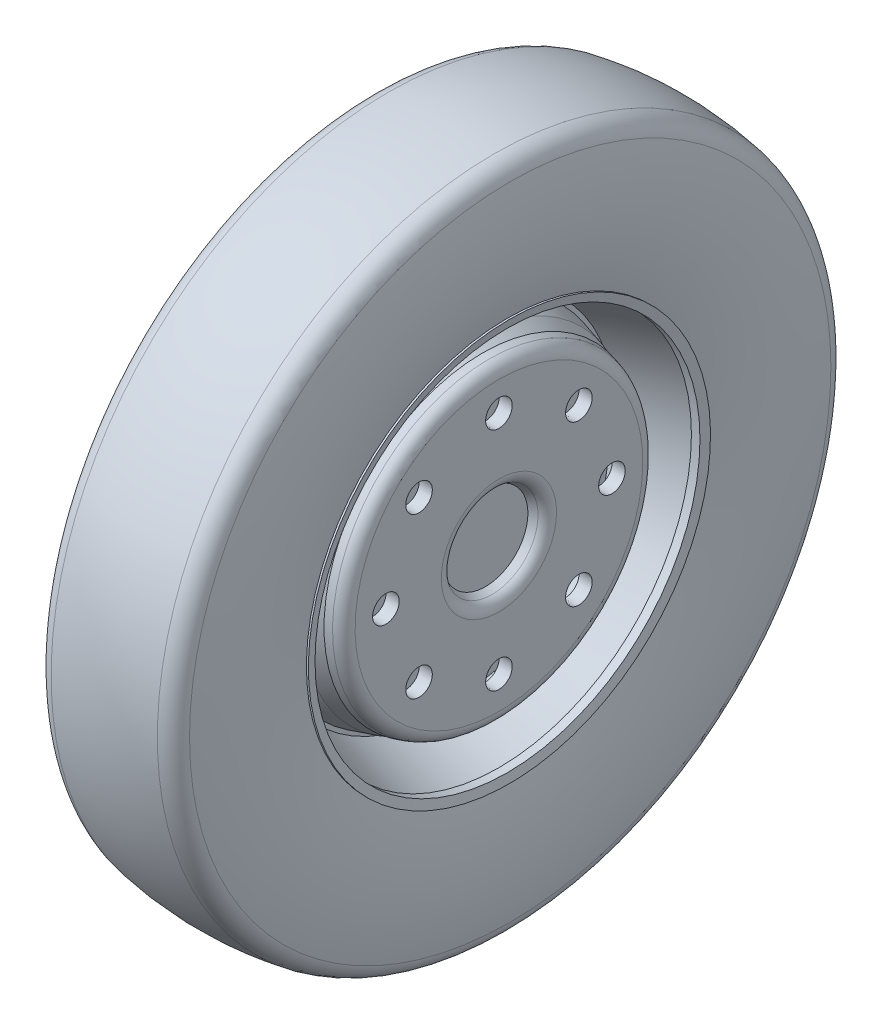
SolidWorks part; units mm, degrees
ref_plane "Front Plane" through (0, 0, 0) normal (0, 0, 1) x (1, 0, 0)
ref_plane "Top Plane" through (0, 0, 0) normal (0, 1, 0) x (1, 0, 0)
ref_plane "Right Plane" through (0, 0, 0) normal (1, 0, 0) x (0, 0, -1)
sketch "Sketch2" plane through (0, 0, 0) normal (0, 0, 1) x (1, 0, 0)
  line L0 (0, 300) -> (0, 212.5441)
  line L1 (0, 300) -> (-28.5605, 300)
  line L2 (-53.1832, 300) -> (-53.1832, 500) construction
  line L3 (-53.1832, 500) -> (146.8168, 500) construction
  line L4 (146.8168, 500) -> (146.8168, 300) construction
  line L5 (46.8168, 259.1719) -> (46.8168, 245.2638)
  line L6 (46.8168, -2.4559) -> (25, -2.4559)
  line L7 (46.8168, 259.1719) -> (133.9688, 287.0687)
  line L8 (133.9688, 287.0687) -> (146.8168, 287.0687)
  line L9 (146.8168, 287.0687) -> (149.7514, 300)
  line L10 (149.7514, 300) -> (146.8168, 300)
  line L11 (48.4269, 252.7294) -> (83.9688, 242.9283)
  line L12 (133.9688, 229.1403) -> (133.9688, 72.3794)
  line L13 (113.8213, -2.4559) -> (46.8168, -2.4559)
  line L14 (0, 212.5441) -> (25, 212.5441)
  line L15 (46.8168, 245.2638) -> (48.4269, 245.2638)
  line L16 (48.4269, 245.2638) -> (48.4269, 252.7294)
  line L17 (113.8213, -2.4559) -> (113.8213, 61.2518)
  line L18 (113.8213, 61.2518) -> (133.9688, 72.3794)
  line L19 (113.8213, 89.4785) -> (113.8213, 205.0209)
  line L20 (113.8213, 205.0209) -> (83.9688, 212.5441)
  line L21 (83.9688, 212.5441) -> (83.9688, 89.4785)
  line L22 (83.9688, 89.4785) -> (113.8213, 89.4785)
  line L23 (83.9688, 242.9283) -> (121.3944, 222.9122)
  line L24 (121.3944, 222.9122) -> (124.7253, 229.1403)
  line L25 (124.7253, 229.1403) -> (109.2667, 233.4031)
  line L26 (109.2667, 233.4031) -> (109.2667, 235.9521)
  line L27 (109.2667, 235.9521) -> (133.9688, 229.1403)
  line L28 (25, 212.5441) -> (25, -2.4559)
  arc A0 (-58.1409, 325) -> (-57.284, 479.9045) centre (385.565, 400) cw
  arc A1 (-33.0877, 504.1008) -> (126.7213, 504.1008) centre (46.8168, 61.2518) cw
  arc A2 (150.9176, 479.9045) -> (146.8168, 300) centre (-291.9314, 400) cw
  arc A3 (-28.5605, 300) -> (-58.1409, 325) centre (-28.5605, 330) cw
  arc A4 (126.7213, 504.1008) -> (150.9176, 479.9045) centre (121.3944, 474.5775) cw
  arc A5 (-57.284, 479.9045) -> (-33.0877, 504.1008) centre (-27.7607, 474.5775) cw
  dimension "D2" = 450
  dimension "D3" = 30
  dimension "D1" = 53.1832
  dimension "D4" = 200
  dimension "D5" = 50
  dimension "D6" = 25
  dimension "D7" = 200
  dimension "D8" = 215
revolve "Revolve1" add sketch "Sketch2" angle 360 about L13
sketch "Sketch3" plane through (133.9688, 0, 0) normal (1, 0, 0) x (0, 0, -1)
  circle A0 centre (0, 170) radius 20
  circle A1 centre (120.2082, 120.2082) radius 20
  circle A2 centre (170, 0) radius 20
  circle A3 centre (120.2082, -120.2082) radius 20
  circle A4 centre (0, -170) radius 20
  circle A5 centre (-120.2082, -120.2082) radius 20
  circle A6 centre (-170, 0) radius 20
  circle A7 centre (-120.2082, 120.2082) radius 20
  dimension "D1" = 40
  dimension "D2" = 170
  dimension "D3" = 8
extrude "Cut-Extrude1" cut sketch "Sketch3" against normal blind 50 draft 1 draft outward yes
fillet "Fillet1" radius 20 2 edges at (133.9688, 229.1403, 0) (133.9688, 72.3794, 0)
sketch "Sketch4" plane through (83.9688, 0, 0) normal (1, 0, 0) x (0, 0, -1)
  circle A0 centre (0, 170) radius 15
  circle A1 centre (120.2082, 120.2082) radius 15
  circle A2 centre (170, 0) radius 15
  circle A3 centre (120.2082, -120.2082) radius 15
  circle A4 centre (0, -170) radius 15
  circle A5 centre (-120.2082, -120.2082) radius 15
  circle A6 centre (-170, 0) radius 15
  circle A7 centre (-120.2082, 120.2082) radius 15
  dimension "D1" = 30
  dimension "D2" = 8
extrude "Cut-Extrude2" cut sketch "Sketch4" against normal through all
